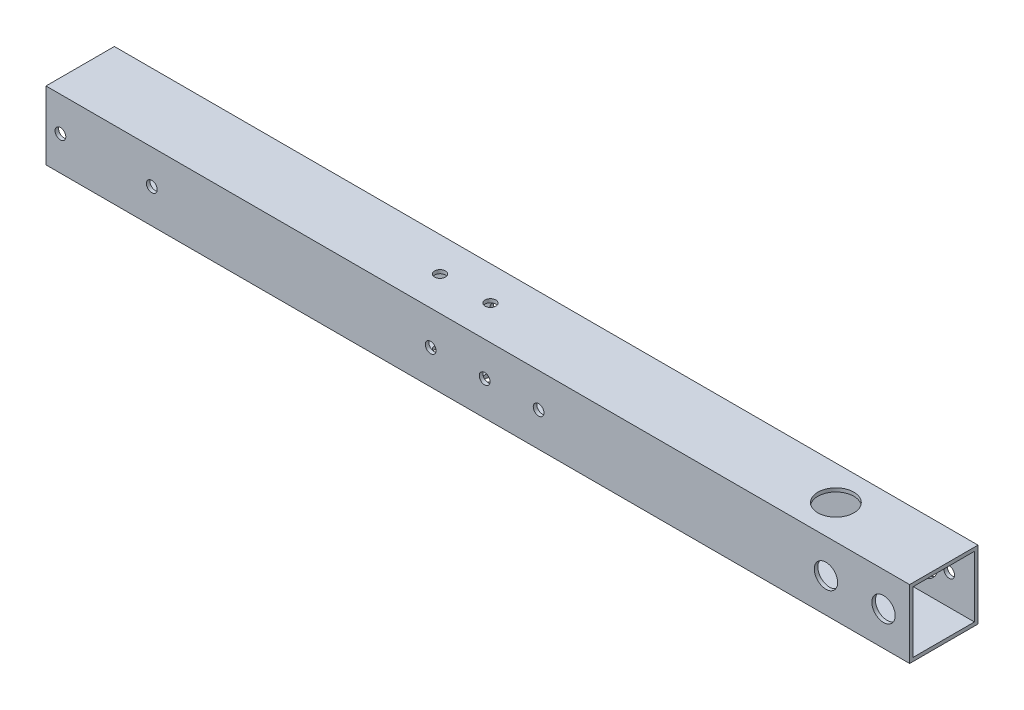
SolidWorks part; units mm, degrees
material "6061 Alloy"
ref_plane "Front Plane" through (0, 0, 0) normal (0, 0, 1) x (1, 0, 0)
ref_plane "Top Plane" through (0, 0, 0) normal (0, 1, 0) x (1, 0, 0)
ref_plane "Right Plane" through (0, 0, 0) normal (1, 0, 0) x (0, 0, -1)
sketch "Sketch1" plane through (0, 0, 0) normal (1, 0, 0) x (0, 0, -1)
  line L0 (-8.5, 8.5) -> (8.5, 8.5)
  line L1 (-9.5, -9.5) -> (9.5, -9.5)
  line L2 (-9.5, -9.5) -> (-9.5, 9.5)
  line L3 (-9.5, 9.5) -> (9.5, 9.5)
  line L4 (9.5, -9.5) -> (9.5, 9.5)
  line L5 (-9.5, -9.5) -> (9.5, 9.5) construction
  line L6 (-9.5, 9.5) -> (9.5, -9.5) construction
  line L7 (8.5, -8.5) -> (8.5, 8.5)
  line L8 (-8.5, -8.5) -> (8.5, -8.5)
  line L9 (-8.5, -8.5) -> (-8.5, 8.5)
  point P0 (0, 0)
  dimension "D1" = 19
  dimension "D2" = 19
  dimension "D3" = 1
extrude "Boss-Extrude1" add sketch "Sketch1" along normal blind 240
sketch "Sketch3" plane through (0, 0, 9.5) normal (0, 0, 1) x (1, 0, 0)
  line L0 (0, 9.5) -> (0, -9.5) construction
  line L1 (25.2651, 0) -> (159.6091, 0) construction
  circle A0 centre (4, 0) radius 1.5
  circle A1 centre (29.4, 0) radius 1.5
  circle A2 centre (106.9, 0) radius 1.5
  circle A3 centre (121.9, 0) radius 1.5
  circle A4 centre (136.9, 0) radius 1.5
  dimension "D1" = 3
  dimension "D4" = 3
  dimension "D7" = 3
  dimension "D2" = 4
  dimension "D5" = 25.4
  dimension "D6" = 77.5
  dimension "D9" = 15
  dimension "D3" = 2
  dimension "D8" = 3
extrude "Cut-Extrude1" cut sketch "Sketch3" against normal through all
sketch "Sketch7" plane through (0, 9.5, 0) normal (0, 1, 0) x (1, 0, 0)
  line L0 (240, 0) -> (0, 0) construction
  line L1 (240, 9.5) -> (240, -9.5) construction
  line L2 (0, 9.5) -> (0, -9.5) construction
  circle A0 centre (100, 0) radius 1.5
  circle A1 centre (114, 0) radius 1.5
  dimension "D2" = 3
  dimension "D1" = 100
  dimension "D4" = 14
  dimension "D3" = 2
extrude "Cut-Extrude5" cut sketch "Sketch7" against normal through all
sketch "Sketch9" plane through (0, 9.5, 0) normal (0, 1, 0) x (1, 0, 0)
  line L0 (240, 0) -> (0, 0) construction
  line L1 (240, 9.5) -> (240, -9.5) construction
  line L2 (0, 9.5) -> (0, -9.5) construction
  circle A0 centre (210, 0) radius 5
  dimension "D1" = 10
  dimension "D2" = 30
extrude "Cut-Extrude6" cut sketch "Sketch9" against normal blind 10
sketch "Sketch10" plane through (0, 0, 9.5) normal (0, 0, 1) x (1, 0, 0)
  line L0 (240, 0) -> (0, 0) construction
  line L1 (240, 9.5) -> (240, -9.5) construction
  line L2 (0, 9.5) -> (0, -9.5) construction
  circle A0 centre (232.75, 0) radius 3.25
  circle A1 centre (216.75, 0) radius 3.25
  dimension "D1" = 6.5
  dimension "D2" = 7.25
  dimension "D4" = 16
  dimension "D3" = 2
extrude "Cut-Extrude7" cut sketch "Sketch10" against normal blind 10
sketch "Sketch11" plane through (0, 0, -9.5) normal (0, 0, -1) x (-1, 0, 0)
  line L0 (0, 0) -> (-240, 0) construction
  line L1 (0, -9.5) -> (0, 9.5) construction
  line L2 (-240, -9.5) -> (-240, 9.5) construction
  circle A0 centre (-225, 0) radius 5
  circle A1 centre (-217, 0) radius 1.5
  circle A2 centre (-233, 0) radius 1.5
  dimension "D1" = 10
  dimension "D4" = 3
  dimension "D5" = 3
  dimension "D2" = 15
  dimension "D3" = 8
  dimension "D6" = 8
extrude "Cut-Extrude8" cut sketch "Sketch11" against normal blind 10
